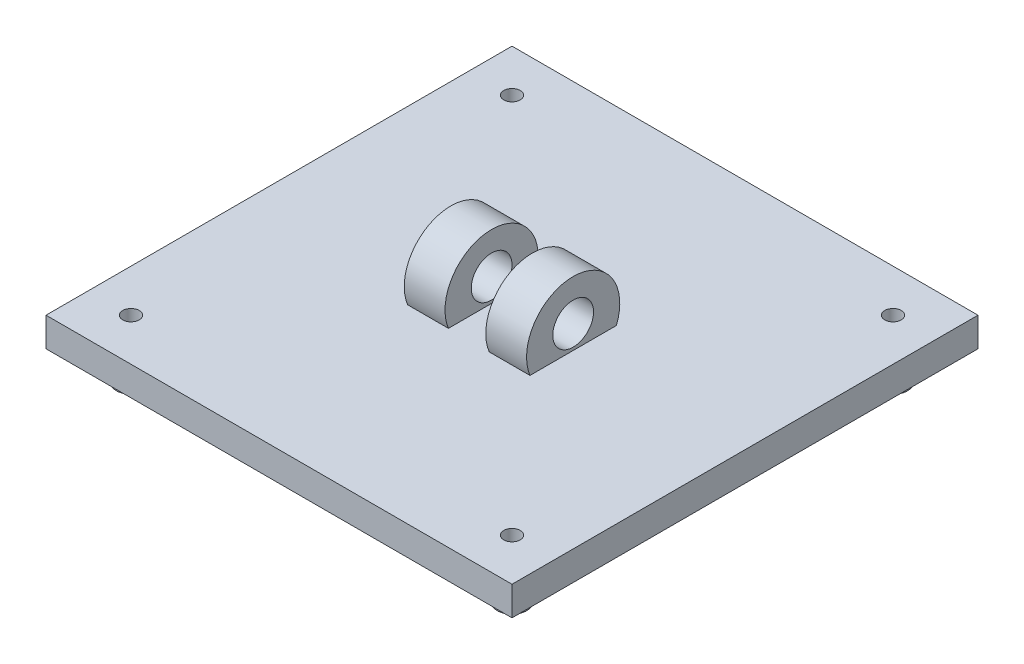
SolidWorks part; units mm, degrees
ref_plane "Front Plane" through (0, 0, 0) normal (0, 0, 1) x (1, 0, 0)
ref_plane "Top Plane" through (0, 0, 0) normal (0, 1, 0) x (1, 0, 0)
ref_plane "Right Plane" through (0, 0, 0) normal (1, 0, 0) x (0, 0, -1)
sketch "Sketch2" plane through (0, 0, 0) normal (0, 1, 0) x (1, 0, 0)
  line L1 (-40, -40) -> (40, -40)
  line L2 (-40, -40) -> (-40, 40)
  line L3 (-40, 40) -> (40, 40)
  line L4 (40, -40) -> (40, 40)
  line L5 (-40, -40) -> (40, 40) construction
  line L6 (-40, 40) -> (40, -40) construction
  point P0 (0, 0)
  dimension "D1" = 80
  dimension "D2" = 80
extrude "Boss-Extrude1" add sketch "Sketch2" along normal blind 5
sketch "Sketch3" plane through (0, 0, 0) normal (1, 0, 0) x (0, 0, -1)
  line L0 (-40, 0) -> (40, 0) construction
  line L1 (0, 0) -> (0.4848, 0)
  circle A0 centre (0, 8) radius 8
  dimension "D1" = 16
  dimension "D2" = 8
extrude "Boss-Extrude2" add sketch "Sketch3" along normal mid plane 21 contours A0
sketch "Sketch4" plane through (0, 0, 0) normal (1, 0, 0) x (0, 0, -1)
  line L0 (-7.4162, 5) -> (7.4162, 5)
  circle A1 centre (0, 8) radius 8
  arc A2 (7.4162, 5) -> (-7.4162, 5) centre (0, 8) ccw construction
extrude "Cut-Extrude3" cut sketch "Sketch4" against normal mid plane 7 contours L0 A1
sketch "Sketch8" plane through (10.5, 0, 0) normal (1, 0, 0) x (0, 0, -1)
  line L1 (7.4162, 5) -> (-7.4162, 5) construction
  circle A0 centre (0, 9) radius 3.5
  dimension "D1" = 7
  dimension "D2" = 4
extrude "Cut-Extrude5" cut sketch "Sketch8" against normal through all
sketch "Sketch9" plane through (0, 0, 0) normal (0, -1, 0) x (1, 0, 0)
  line L0 (0, 0) -> (0, -40)
  line L1 (40, -40) -> (-40, -40) construction
  circle A0 centre (-32.705, 32.705) radius 2.5
  circle A1 centre (32.705, 32.705) radius 2.5
  circle A2 centre (-32.705, -32.705) radius 2.5
  circle A3 centre (32.705, -32.705) radius 2.5
  point P13 (0, 0)
  point P14 (0, 0)
  dimension "D2" = 32.705
  dimension "D3" = 5
  dimension "D5" = 32.705
  dimension "D1" = 32.705
  dimension "D4" = 32.705
extrude "Boss-Extrude3" add sketch "Sketch9" along normal blind 5 contours A0 | A1 | A3 | A2
sketch "Sketch10" plane through (0, -5, 0) normal (0, -1, 0) x (1, 0, 0)
  circle A0 centre (-32.705, -32.705) radius 1.41
  circle A1 centre (-32.705, 32.705) radius 1.41
  circle A2 centre (32.705, 32.705) radius 1.41
  circle A3 centre (32.705, -32.705) radius 1.41
  dimension "D1" = 2.82
extrude "Cut-Extrude6" cut sketch "Sketch10" against normal through all
equation "\"D2@Sketch3\"=\"D1@Sketch3\"/2"
